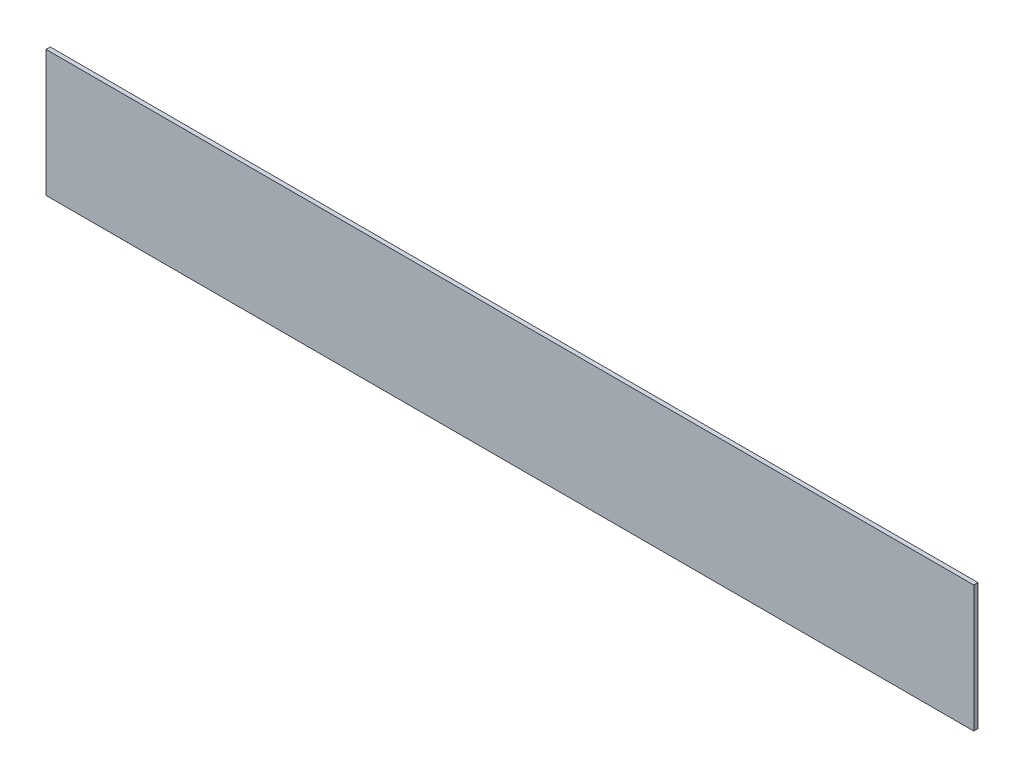
SolidWorks part; units mm, degrees
ref_plane "Front Plane" through (0, 0, 0) normal (0, 0, 1) x (1, 0, 0)
ref_plane "Top Plane" through (0, 0, 0) normal (0, 1, 0) x (1, 0, 0)
ref_plane "Right Plane" through (0, 0, 0) normal (1, 0, 0) x (0, 0, -1)
sketch "Sketch1" plane through (0, 0, 0) normal (0, 0, 1) x (1, 0, 0)
  line L1 (0, 0) -> (558.8, 0)
  line L2 (0, 0) -> (0, 76.2)
  line L3 (0, 76.2) -> (558.8, 76.2)
  line L4 (558.8, 0) -> (558.8, 76.2)
  dimension "D1" = 558.8
  dimension "D2" = 76.2
extrude "Boss-Extrude1" add sketch "Sketch1" along normal blind 2.54
